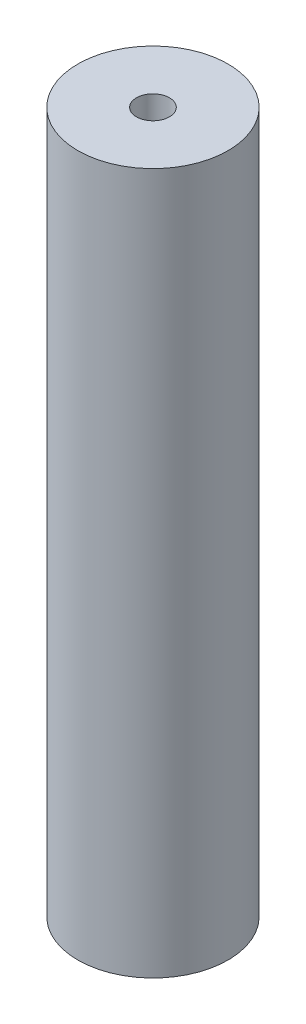
SolidWorks part; units mm, degrees
material "5052-H34"
ref_plane "正面" through (0, 0, 0) normal (0, 0, 1) x (1, 0, 0)
ref_plane "平面" through (0, 0, 0) normal (0, 1, 0) x (1, 0, 0)
ref_plane "右側面" through (0, 0, 0) normal (1, 0, 0) x (0, 0, -1)
sketch "ｽｹｯﾁ1" plane through (0, 0, 0) normal (0, 1, 0) x (1, 0, 0)
  circle A0 centre (0, 0) radius 7.5
  dimension "D1" = 15
extrude "ﾎﾞｽ - 押し出し1" add sketch "ｽｹｯﾁ1" along normal blind 70
hole_wizard "M4x0.7 ねじ穴1" positions "ｽｹｯﾁ2" profile "ｽｹｯﾁ3" tap size "M4x0.7" standard "JIS"
sketch "ｽｹｯﾁ2" plane through (0, 70, 0) normal (0, 1, 0) x (1, 0, 0)
  point P0 (0, 0)
sketch "ｽｹｯﾁ3" plane through (0, 70, 0) normal (1, 0, 0) x (0, 0, 1)
  line L0 (0, 0) -> (0, 20.9914)
  line L1 (0, 20.9914) -> (1.65, 20)
  line L2 (1.65, 20) -> (1.65, 0)
  line L5 (1.65, 0) -> (0, 0)
  line L10 (0, 20.9914) -> (-1.65, 20) construction
  line L11 (0, -6.35) -> (0, 107.95) construction
  dimension "ねじ下穴ﾄﾞﾘﾙ直径" = 3.3
  dimension "ねじ下穴ﾄﾞﾘﾙの深さ" = 20
  dimension "ﾄﾞﾘﾙ角度" = 118
ref_plane "平面1" through (0, 35, 0) normal (0, 1, 0) x (1, 0, 0)
mirror "ﾐﾗｰ1" about plane through (0, 35, 0) normal (0, 1, 0) of "M4x0.7 ねじ穴1"
